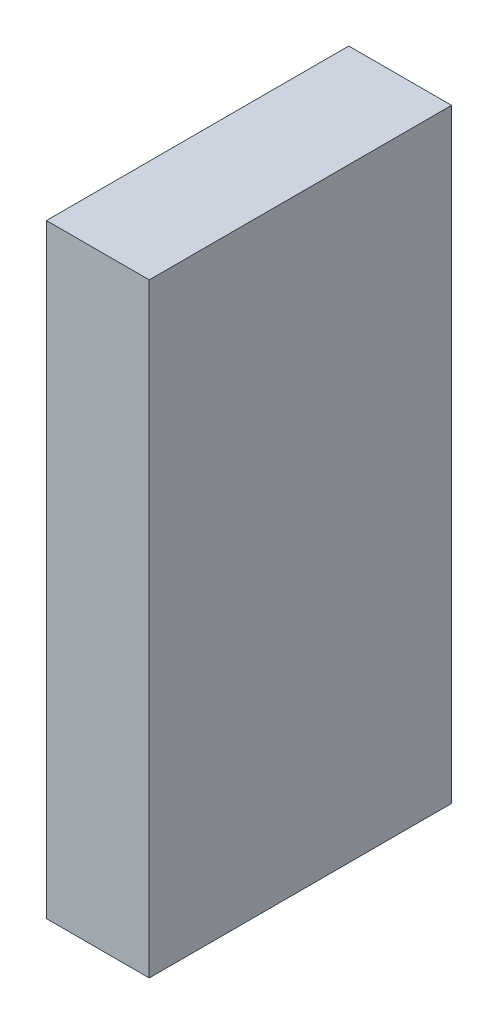
SolidWorks part; units mm, degrees
ref_plane "Front Plane" through (0, 0, 0) normal (0, 0, 1) x (1, 0, 0)
ref_plane "Top Plane" through (0, 0, 0) normal (0, 1, 0) x (1, 0, 0)
ref_plane "Right Plane" through (0, 0, 0) normal (1, 0, 0) x (0, 0, -1)
sketch "Sketch1" plane through (0, 0, 0) normal (0, 1, 0) x (1, 0, 0)
  line L1 (-93.2376, 21.9059) -> (-76.2376, 21.9059)
  line L2 (-93.2376, 21.9059) -> (-93.2376, -28.0941)
  line L3 (-93.2376, -28.0941) -> (-76.2376, -28.0941)
  line L4 (-76.2376, 21.9059) -> (-76.2376, -28.0941)
  dimension "D1" = 17
  dimension "D2" = 50
extrude "Boss-Extrude1" add sketch "Sketch1" along normal blind 100
